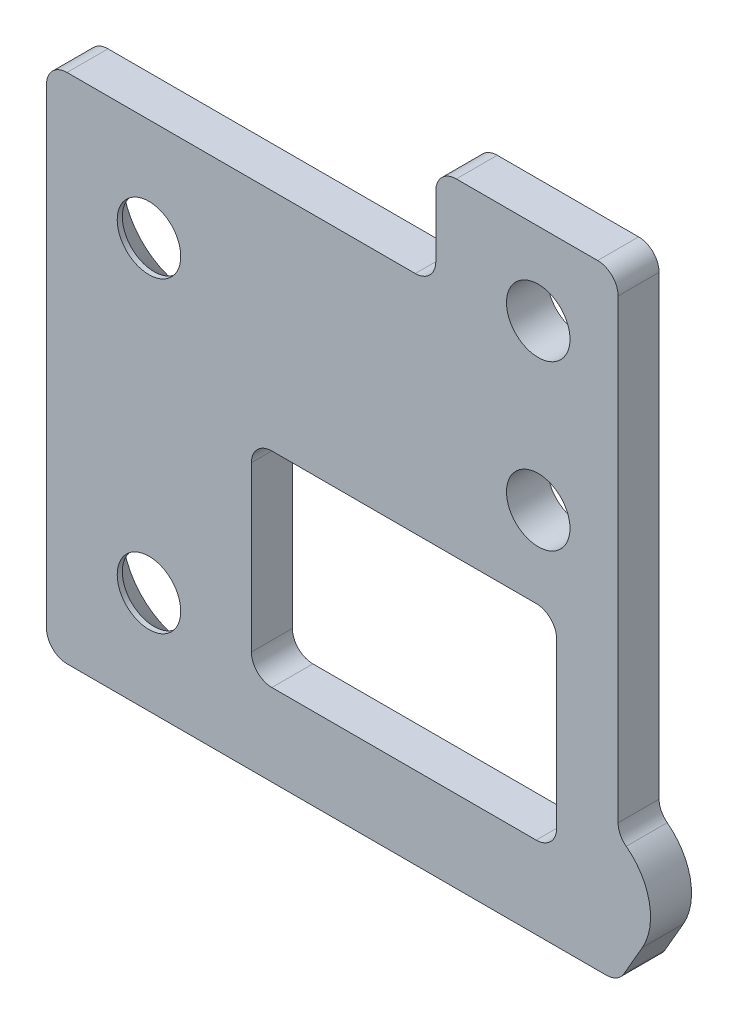
SolidWorks part; units mm, degrees
material "环氧树脂,未充填"
ref_plane "前视基准面" through (0, 0, 0) normal (0, 0, 1) x (1, 0, 0)
ref_plane "上视基准面" through (0, 0, 0) normal (0, 1, 0) x (1, 0, 0)
ref_plane "右视基准面" through (0, 0, 0) normal (1, 0, 0) x (0, 0, -1)
sketch "草图1" plane through (0, 0, 0) normal (0, 0, 1) x (1, 0, 0)
  line L0 (0, 0) -> (-12.4728, 0) construction
  line L1 (9.5, -12.5) -> (-9.5, -12.5)
  line L2 (9.5, -12.5) -> (9.5, 12.5) construction
  line L3 (9.5, 12.5) -> (-9.5, 12.5)
  line L4 (-9.5, -12.5) -> (-9.5, 12.5)
  line L5 (9.5, -12.5) -> (-9.5, 12.5) construction
  line L6 (9.5, 12.5) -> (-9.5, -12.5) construction
  line L7 (9.5, 12.5) -> (9.5, 17.5)
  line L8 (9.5, 17.5) -> (18.4, 17.5)
  line L9 (18.4, 17.5) -> (18.4, 2.5)
  line L10 (18.4, 2.5) -> (9.5, 2.5) construction
  line L12 (9.5, -12.5) -> (18.4, -12.5)
  line L13 (18.4, -12.5) -> (22.7301, -5)
  line L14 (22.7301, -5) -> (18.4, -7.5)
  line L16 (18.4, 2.5) -> (18.4, -7.5)
  line L17 (15.4, -8.5) -> (0.5, -8.5)
  line L18 (15.4, -8.5) -> (15.4, 1.5)
  line L19 (15.4, 1.5) -> (0.5, 1.5)
  line L20 (0.5, -8.5) -> (0.5, 1.5)
  line L21 (15.4, -8.5) -> (0.5, 1.5) construction
  line L22 (15.4, 1.5) -> (0.5, -8.5) construction
  circle A0 centre (14.5, 13.5) radius 1.55
  circle A1 centre (14.5, 5.5) radius 1.55
  circle A2 centre (-4.5, 7.5) radius 1.55
  circle A3 centre (-4.5, -7.5) radius 1.55
  point P0 (0, 0)
  point P22 (7.95, -3.5)
  dimension "D1" = 3.1
  dimension "D7" = 3.1
  dimension "D2" = 8
  dimension "D3" = 25
  dimension "D4" = 19
  dimension "D5" = 15
  dimension "D6" = 5
  dimension "D8" = 5
  dimension "D9" = 3.9
  dimension "D10" = 4
  dimension "D11" = 3
  dimension "D12" = 1
  dimension "D13" = 60
  dimension "D14" = 5
  dimension "D15" = 60
  dimension "D16" = 4
  dimension "D17" = 4
  dimension "D18" = 5
  dimension "D19" = 3
extrude "凸台-拉伸1" add sketch "草图1" along normal blind 2
fillet "圆角1" radius 1 11 edges at (9.5, 12.5, 1) (9.5, 17.5, 1) (18.4, 17.5, 1) (18.4, -7.5, 1) (18.4, -12.5, 1) (-9.5, -12.5, 1) (-9.5, 12.5, 1) (15.4, -8.5, 1) (15.4, 1.5, 1) (0.5, -8.5, 1) (0.5, 1.5, 1)
hole_wizard "打孔尺寸(%根据十字)槽沉头木螺钉的类型1" positions "3D草图1" profile "草图2" countersink size "M3" standard "GB" end condition through all
sketch3d "3D草图1"
  line L0 (-4.5, 7.5, 2) -> (-4.5, 7.5, 0) construction
  line L1 (-4.5, -7.5, 2) -> (-4.5, -7.5, 0) construction
  point P0 (-4.5, 7.5, 0)
  point P4 (-4.5, -7.5, 0)
sketch "草图2" plane through (-4.5, 7.5, 0) normal (1, 0, 0) x (0, 1, 0)
  line L0 (0, 0) -> (0, 2)
  line L1 (0, 2) -> (1.55, 2)
  line L2 (1.55, 2) -> (1.55, 1.75)
  line L3 (1.55, 1.75) -> (3.3, 0)
  line L5 (3.3, 0) -> (0, 0)
  line L6 (-1.55, 1.75) -> (-3.3, 0) construction
  line L11 (0, -6.35) -> (0, 107.95) construction
  dimension "通孔孔直径" = 3.1
  dimension "通孔孔深度" = 2
  dimension "近端锥形沉头孔直径" = 6.6
  dimension "近端锥形沉头孔角度" = 90
fillet "圆角2" radius 3 1 edges at (22.7301, -5, 1)
